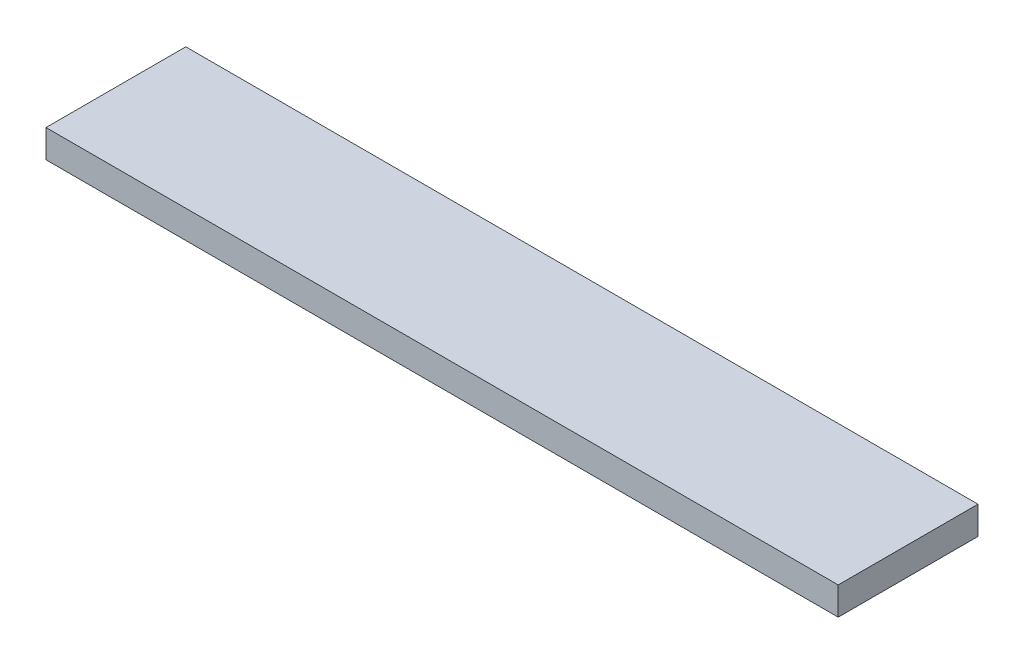
SolidWorks part; units mm, degrees
material "Acrílico (médio-alto impacto)"
ref_plane "Plano frontal" through (0, 0, 0) normal (0, 0, 1) x (1, 0, 0)
ref_plane "Plano superior" through (0, 0, 0) normal (0, 1, 0) x (1, 0, 0)
ref_plane "Plano direito" through (0, 0, 0) normal (1, 0, 0) x (0, 0, -1)
sketch "Esboço1" plane through (0, 0, 0) normal (0, 1, 0) x (1, 0, 0)
  line L1 (-170, -30) -> (170, -30)
  line L2 (-170, -30) -> (-170, 30)
  line L3 (-170, 30) -> (170, 30)
  line L4 (170, -30) -> (170, 30)
  line L5 (-170, -30) -> (170, 30) construction
  line L6 (-170, 30) -> (170, -30) construction
  point P0 (0, 0)
  dimension "D1" = 340
  dimension "D2" = 60
extrude "Ressalto-extrusão1" add sketch "Esboço1" along normal blind 12
